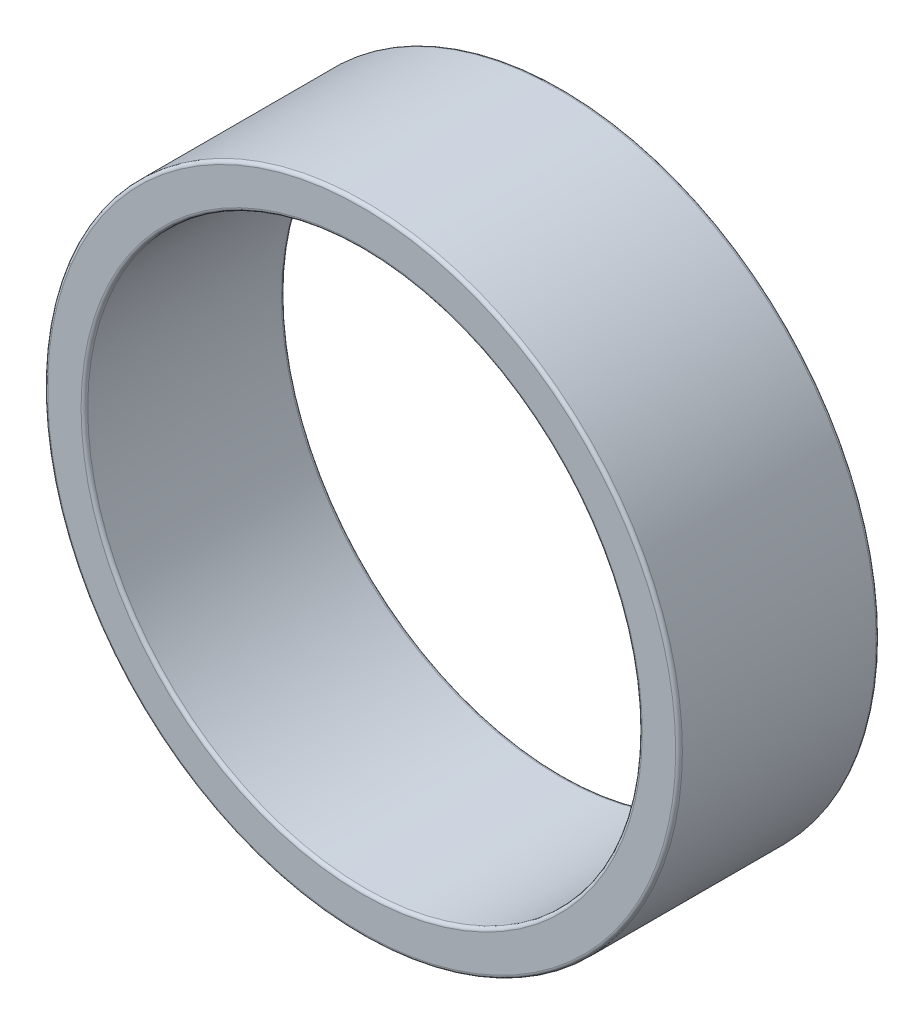
SolidWorks part; units mm, degrees
ref_plane "Front Plane" through (0, 0, 0) normal (0, 0, 1) x (1, 0, 0)
ref_plane "Top Plane" through (0, 0, 0) normal (0, 1, 0) x (1, 0, 0)
ref_plane "Right Plane" through (0, 0, 0) normal (1, 0, 0) x (0, 0, -1)
sketch "Sketch1" plane through (0, 0, 0) normal (0, 0, 1) x (1, 0, 0)
  circle A0 centre (0, 0) radius 9.5
  circle A1 centre (0, 0) radius 8.3
  dimension "D1" = 19
  dimension "D2" = 1.2
extrude "Boss-Extrude1" add sketch "Sketch1" along normal blind 6
fillet "Fillet1" radius 0.1 4 edges at (9.5, 0, 0) (8.3, 0, 0) (8.3, 0, 6) (9.5, 0, 6)
